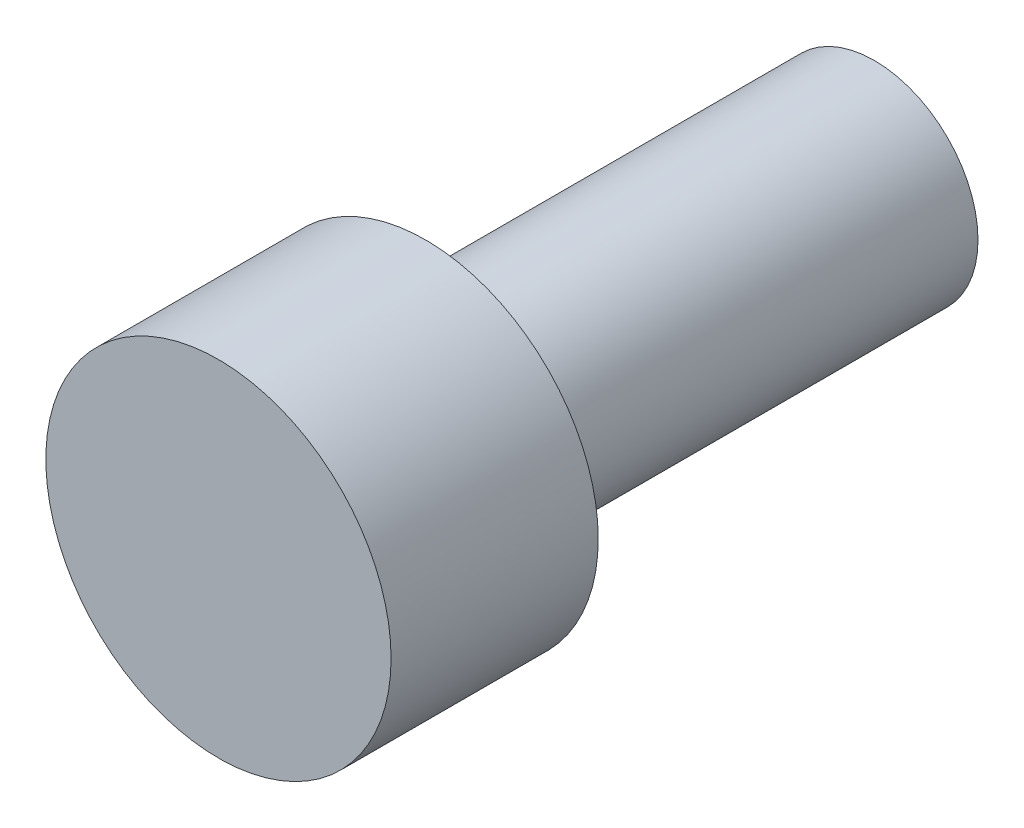
SolidWorks part; units mm, degrees
ref_plane "前视基准面" through (0, 0, 0) normal (0, 0, 1) x (1, 0, 0)
ref_plane "上视基准面" through (0, 0, 0) normal (0, 1, 0) x (1, 0, 0)
ref_plane "右视基准面" through (0, 0, 0) normal (1, 0, 0) x (0, 0, -1)
other "Configuration Table"
sketch "草图1" plane through (0, 0, 0) normal (0, 1, 0) x (1, 0, 0)
  line L0 (-2.8562, 0) -> (-2.8562, 6.2625) construction
  line L1 (-2.8562, 18.7) -> (-5.8563, 18.7)
  line L2 (-5.8563, 18.7) -> (-5.8562, 5.7)
  line L3 (-5.8562, 5.7) -> (-7.8563, 5.7)
  line L4 (-7.8563, 5.7) -> (-7.8563, -0.3)
  line L5 (-7.8563, -0.3) -> (-2.8562, -0.3)
  line L6 (-2.8562, 18.7) -> (-2.8562, -0.3)
  dimension "D1" = 6
  dimension "D2" = 13
  dimension "D3" = 6
  dimension "D4" = 10
revolve "旋转1" add sketch "草图1" angle 360 about L0
